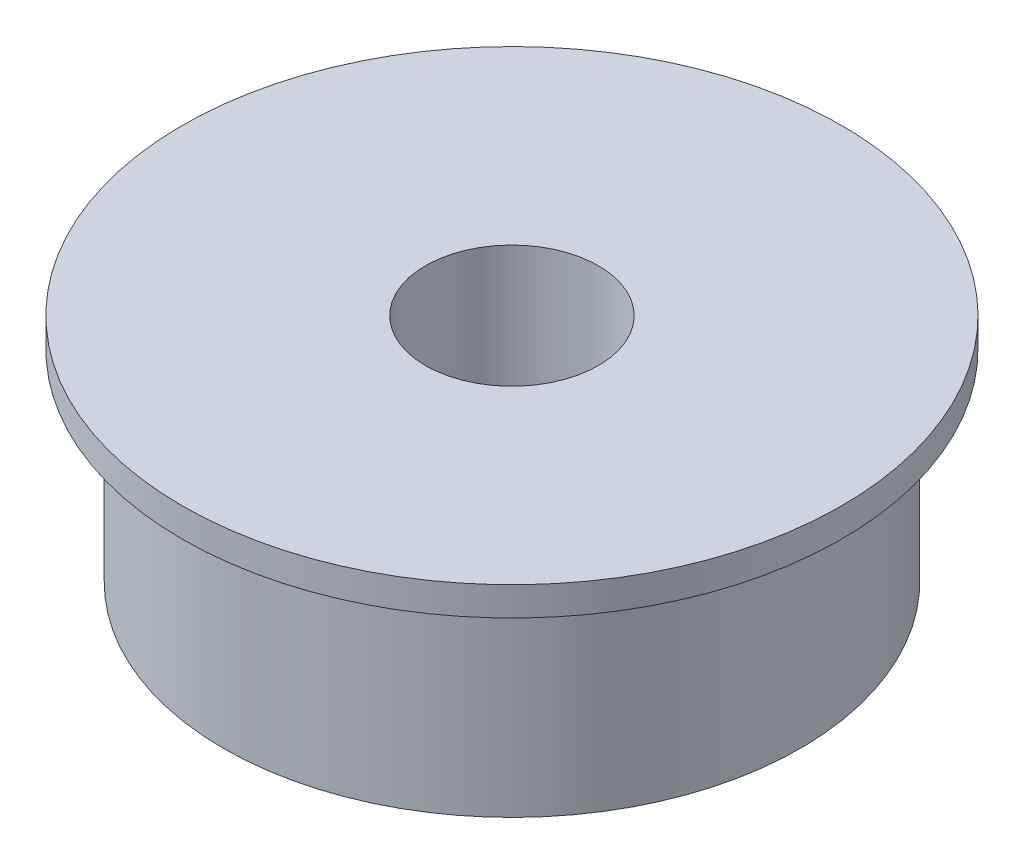
SolidWorks part; units mm, degrees
ref_plane "Front Plane" through (0, 0, 0) normal (0, 0, 1) x (1, 0, 0)
ref_plane "Top Plane" through (0, 0, 0) normal (0, 1, 0) x (1, 0, 0)
ref_plane "Right Plane" through (0, 0, 0) normal (1, 0, 0) x (0, 0, -1)
sketch "Sketch1" plane through (0, 0, 0) normal (0, 1, 0) x (1, 0, 0)
  circle A0 centre (0, 0) radius 5
  dimension "D1" = 10
extrude "Boss-Extrude1" add sketch "Sketch1" along normal blind 3.5
sketch "Sketch2" plane through (0, 3.5, 0) normal (0, 1, 0) x (1, 0, 0)
  circle A0 centre (0, 0) radius 5.715
  dimension "D1" = 11.43
extrude "Boss-Extrude2" add sketch "Sketch2" along normal blind 0.5005
sketch "Sketch3" plane through (0, 4.0005, 0) normal (0, 1, 0) x (1, 0, 0)
  circle A0 centre (0, 0) radius 1.5
  dimension "D1" = 3
extrude "Cut-Extrude1" cut sketch "Sketch3" against normal up to next
equation "\"thin_thickness\"=0.137795"
equation "\"D1@Boss-Extrude1\"=\"thin_thickness\""
equation "\"D1@Boss-Extrude2\"= .1575 - \"thin_thickness\""
